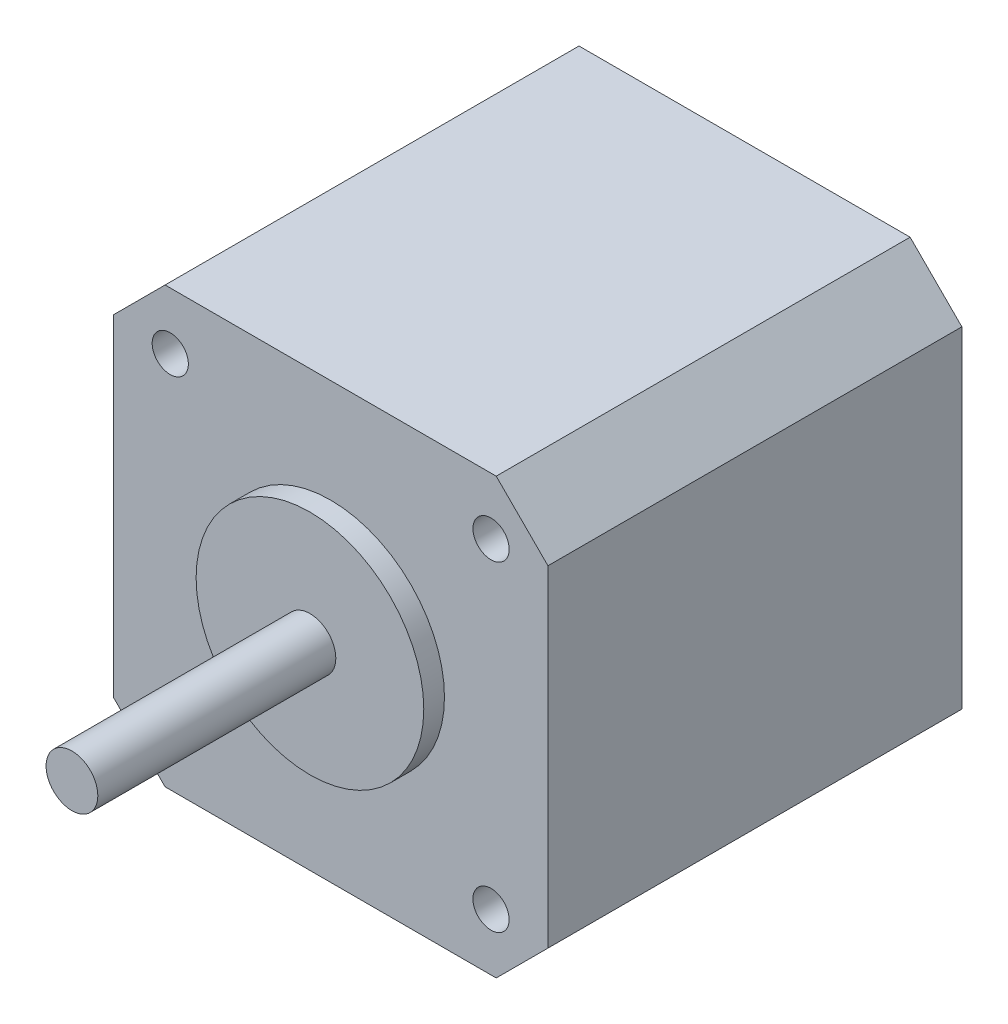
SolidWorks part; units mm, degrees
ref_plane "前基準面" through (0, 0, 0) normal (0, 0, 1) x (1, 0, 0)
ref_plane "上基準面" through (0, 0, 0) normal (0, 1, 0) x (1, 0, 0)
ref_plane "右基準面" through (0, 0, 0) normal (1, 0, 0) x (0, 0, -1)
sketch "草圖1" plane through (0, 0, 0) normal (0, 0, 1) x (1, 0, 0)
  line L1 (-21, 21) -> (21, 21)
  line L2 (-21, 21) -> (-21, -21)
  line L3 (-21, -21) -> (21, -21)
  line L4 (21, 21) -> (21, -21)
  point P4 (0, 21)
  point P6 (-21, 0)
  dimension "D1" = 42
  dimension "D2" = 42
extrude "填料-伸長1" add sketch "草圖1" along normal blind 40
chamfer "導角1" distance 5 angle 45 4 edges at (-21, -21, 20) (21, -21, 20) (21, 21, 20) (-21, 21, 20)
sketch "草圖2" plane through (0, 0, 40) normal (0, 0, 1) x (1, 0, 0)
  circle A0 centre (0, 0) radius 11
  dimension "D1" = 22
extrude "填料-伸長2" add sketch "草圖2" along normal blind 2
sketch "草圖3" plane through (0, 0, 42) normal (0, 0, 1) x (1, 0, 0)
  circle A0 centre (0, 0) radius 2.5
  dimension "D1" = 5
extrude "填料-伸長3" add sketch "草圖3" along normal blind 23
sketch "草圖4" plane through (0, 0, 40) normal (0, 0, 1) x (1, 0, 0)
  line L0 (-21, 16) -> (-21, -16) construction
  line L1 (16, 21) -> (-16, 21) construction
  line L2 (0, 21) -> (0, -21) construction
  line L3 (-16, -21) -> (16, -21) construction
  line L4 (0, -21) -> (21, 0) construction
  line L5 (21, -16) -> (21, 16) construction
  line L6 (21, 0) -> (-21, 0) construction
  circle A0 centre (-15.5, 15.5) radius 1.75
  circle A1 centre (-15.5, -15.5) radius 1.75
  circle A2 centre (15.5, -15.5) radius 1.75
  circle A3 centre (15.5, 15.5) radius 1.75
  dimension "D1" = 3.5
  dimension "D2" = 5.5
  dimension "D3" = 5.5
  dimension "D4" = 31
extrude "除料-伸長1" cut sketch "草圖4" against normal blind 3
